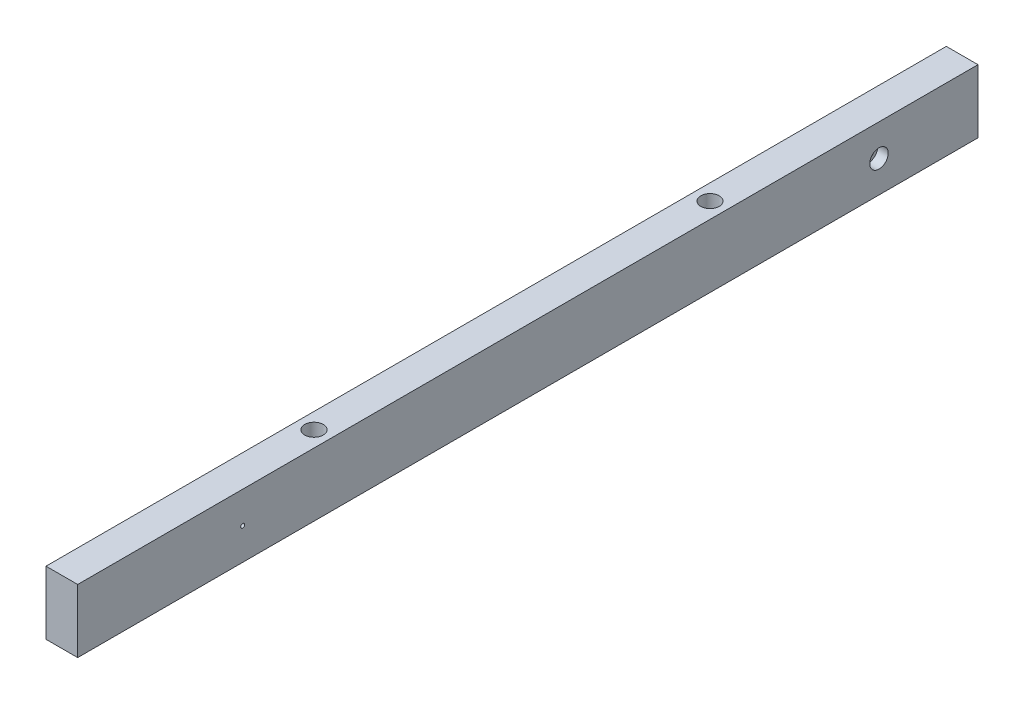
SolidWorks part; units mm, degrees
material "Sapin"
ref_plane "Plan de face" through (0, 0, 0) normal (0, 0, 1) x (1, 0, 0)
ref_plane "Plan de dessus" through (0, 0, 0) normal (0, 1, 0) x (1, 0, 0)
ref_plane "Plan de droite" through (0, 0, 0) normal (1, 0, 0) x (0, 0, -1)
sketch "Esquisse1" plane through (0, 0, 0) normal (1, 0, 0) x (0, 0, -1)
  line L1 (341, -24) -> (341, 24)
  line L2 (341, -24) -> (-341, -24)
  line L3 (-341, -24) -> (-341, 24)
  line L4 (341, 24) -> (-341, 24)
  line L5 (341, -24) -> (-341, 24) construction
  line L6 (-341, -24) -> (341, 24) construction
  point P0 (0, 0)
  dimension "D1" = 48
  dimension "D2" = 682
extrude "Boss.-Extru.1" add sketch "Esquisse1" along normal blind 24
sketch "Esquisse2" plane through (0, -24, 0) normal (0, -1, 0) x (1, 0, 0)
  line L0 (0, 0) -> (24, 0) construction
  line L1 (24, 341) -> (24, -341) construction
  line L2 (12, 341) -> (12, -341) construction
  line L3 (24, 341) -> (0, 341) construction
  line L4 (24, -341) -> (0, -341) construction
  circle A0 centre (12, 150) radius 4.5
  circle A1 centre (12, -150) radius 4.5
  dimension "D2" = 9
  dimension "D1" = 300
extrude "Enlèv. mat.-Extru.1" cut sketch "Esquisse2" against normal through all
sketch "Esquisse3" plane through (0, -24, 0) normal (0, -1, 0) x (1, 0, 0)
  circle A0 centre (12, 150) radius 10
  circle A1 centre (12, -150) radius 10
  dimension "D1" = 20
extrude "Enlèv. mat.-Extru.2" cut sketch "Esquisse3" against normal blind 10
sketch "Esquisse4" plane through (0, 24, 0) normal (0, 1, 0) x (-1, 0, 0)
  circle A0 centre (-12, 150) radius 7
  circle A1 centre (-12, -150) radius 7
  dimension "D1" = 14
extrude "Enlèv. mat.-Extru.3" cut sketch "Esquisse4" against normal blind 10
sketch "Esquisse5" plane through (24, 0, 0) normal (1, 0, 0) x (0, 0, -1)
  line L0 (-341, 24) -> (-341, -24) construction
  circle A0 centre (-216, 0) radius 1.5
  dimension "D1" = 3
  dimension "D2" = 125
extrude "Enlèv. mat.-Extru.4" cut sketch "Esquisse5" against normal through all
sketch "Esquisse6" plane through (0, 0, 0) normal (-1, 0, 0) x (0, 0, 1)
  line L0 (-341, -24) -> (-341, 24) construction
  circle A0 centre (-266, 0) radius 4.5
  dimension "D1" = 9
  dimension "D2" = 75
extrude "Enlèv. mat.-Extru.5" cut sketch "Esquisse6" against normal through all
sketch "Esquisse7" plane through (24, 0, 0) normal (-1, 0, 0) x (0, 0, 1)
  circle A0 centre (-266, 0) radius 7
  dimension "D1" = 14
extrude "Enlèv. mat.-Extru.6" cut sketch "Esquisse7" along normal blind 8
sketch "Esquisse8" [suppressed] plane through (0, 0, 0) normal (1, 0, 0) x (0, 0, -1)
  circle A0 centre (216, 0) radius 7
  dimension "D1" = 14
extrude "Enlèv. mat.-Extru.7" [suppressed] cut sketch "Esquisse8" along normal blind 8
